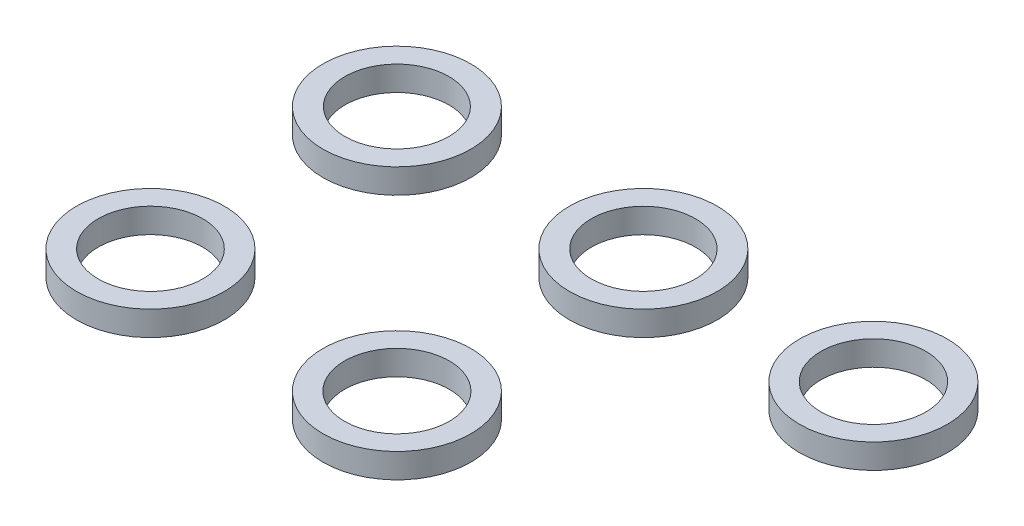
SolidWorks part; units mm, degrees
ref_plane "Front Plane" through (0, 0, 0) normal (0, 0, 1) x (1, 0, 0)
ref_plane "Top Plane" through (0, 0, 0) normal (0, 1, 0) x (1, 0, 0)
ref_plane "Right Plane" through (0, 0, 0) normal (1, 0, 0) x (0, 0, -1)
sketch "Sketch1" plane through (0, 0, 0) normal (0, 1, 0) x (1, 0, 0)
  circle A0 centre (0, 0) radius 15
  circle A1 centre (50, 0) radius 15
  circle A3 centre (0, -50) radius 15
  circle A4 centre (50, -50) radius 15
  circle A6 centre (0, 0) radius 10.55
  circle A7 centre (50, 0) radius 10.575
  circle A8 centre (0, -50) radius 10.6
  circle A9 centre (50, -50) radius 10.625
  circle A10 centre (96.6724, 0) radius 15
  circle A11 centre (96.6724, 0) radius 10.65
  dimension "D1" = 30
  dimension "D2" = 30
  dimension "D3" = 21.2
  dimension "D4" = 30
  dimension "D5" = 30
  dimension "D6" = 21.25
  dimension "D9" = 21.3
  dimension "D10" = 21.1
  dimension "D11" = 21.15
  dimension "D8" = 30
  dimension "D7" = 50
extrude "Boss-Extrude1" add sketch "Sketch1" along normal blind 5
